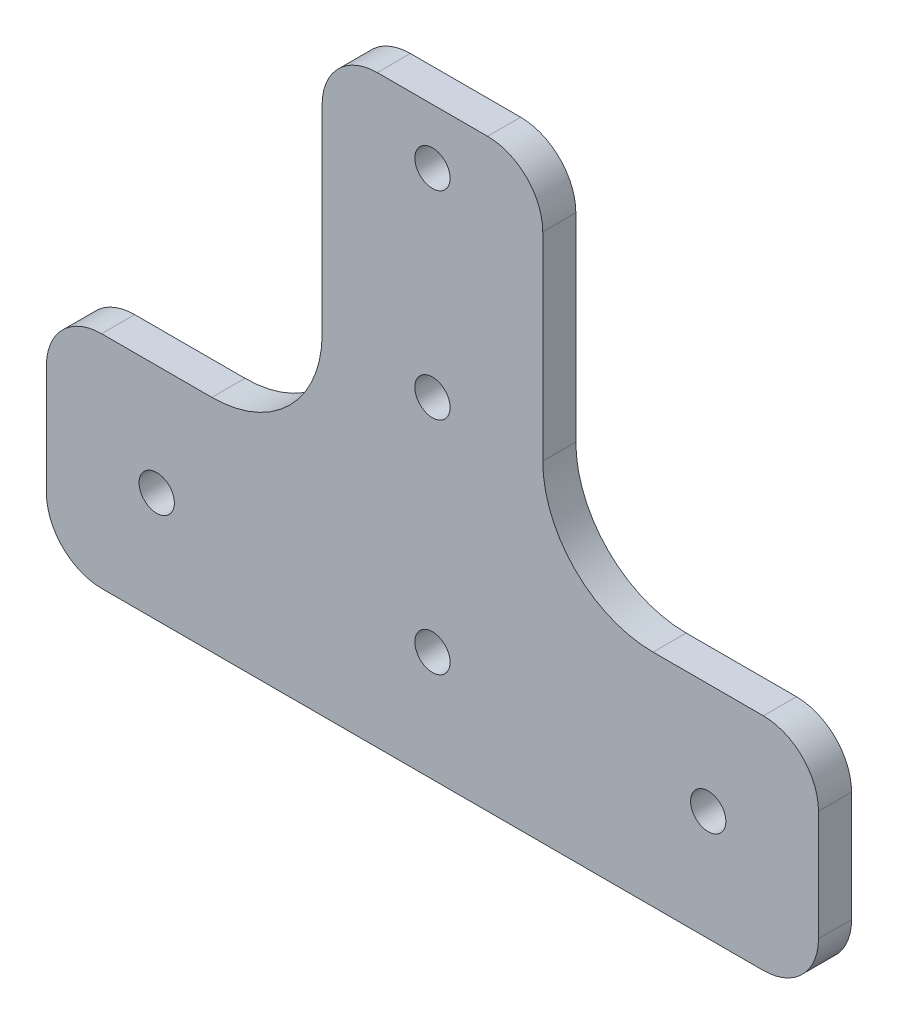
SolidWorks part; units mm, degrees
material "Thornel Mat VMA"
ref_plane "前视基准面" through (0, 0, 0) normal (0, 0, 1) x (1, 0, 0)
ref_plane "上视基准面" through (0, 0, 0) normal (0, 1, 0) x (1, 0, 0)
ref_plane "右视基准面" through (0, 0, 0) normal (1, 0, 0) x (0, 0, -1)
other "Configuration Table"
sketch "草图1" plane through (0, 0, 0) normal (0, 0, 1) x (1, 0, 0)
  line L1 (0, 0) -> (20, 0)
  line L2 (0, 0) -> (0, 53)
  line L3 (0, 53) -> (20, 53)
  line L4 (20, 0) -> (20, 53)
  dimension "D1" = 20
  dimension "D2" = 53
extrude "凸台-拉伸1" add sketch "草图1" along normal blind 3
sketch "草图2" plane through (0, 0, 3) normal (0, 0, 1) x (1, 0, 0)
  line L0 (0, 0) -> (20, 0) construction
  line L1 (-25, 0) -> (45, 0)
  line L2 (-25, 0) -> (-25, 20)
  line L3 (-25, 20) -> (45, 20)
  line L4 (45, 0) -> (45, 20)
  line L5 (10, 0) -> (10, 53) construction
  line L6 (20, 53) -> (0, 53) construction
  line L7 (20, 0) -> (20, 53) construction
  dimension "D1" = 20
  dimension "D2" = 25
extrude "凸台-拉伸2" add sketch "草图2" against normal blind 3
sketch "草图3" plane through (0, 0, 3) normal (0, 0, 1) x (1, 0, 0)
  line L0 (10, 0) -> (10, 53) construction
  line L1 (-25, 0) -> (45, 0) construction
  line L2 (20, 53) -> (0, 53) construction
  line L3 (-25, 10) -> (45, 10) construction
  line L4 (-25, 20) -> (-25, 0) construction
  line L5 (45, 0) -> (45, 20) construction
  circle A0 centre (10, 48) radius 1.6
  circle A1 centre (10, 30) radius 1.6
  circle A2 centre (10, 10) radius 1.6
  circle A3 centre (-15, 10) radius 1.6
  circle A4 centre (35, 10) radius 1.6
  dimension "D1" = 3.2
  dimension "D2" = 18
  dimension "D3" = 5
  dimension "D4" = 25
  dimension "D5" = 25
extrude "切除-拉伸1" cut sketch "草图3" against normal through all
fillet "圆角1" radius 10 2 edges at (20, 20, 1.5) (0, 20, 1.5)
fillet "圆角2" radius 5 6 edges at (20, 53, 1.5) (45, 20, 1.5) (45, 0, 1.5) (-25, 0, 1.5) (-25, 20, 1.5) (0, 53, 1.5)
